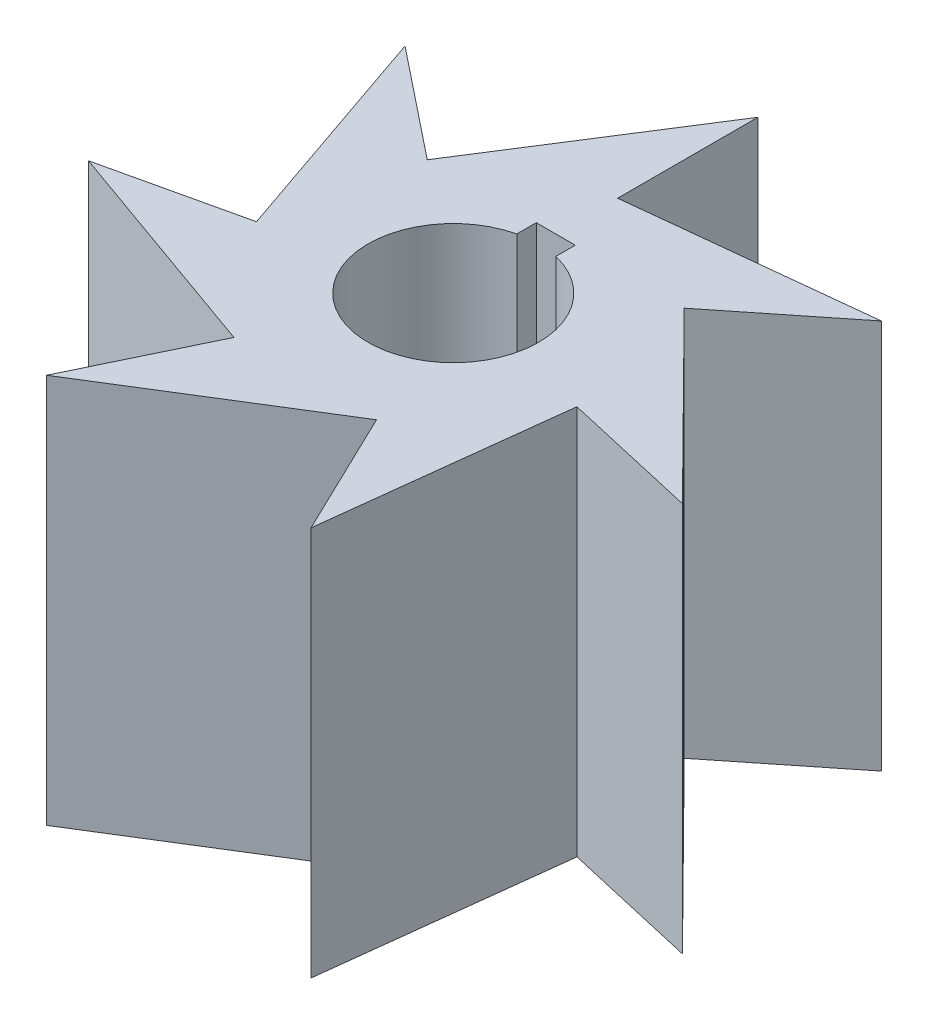
SolidWorks part; units mm, degrees
ref_plane "Front Plane" through (0, 0, 0) normal (0, 0, 1) x (1, 0, 0)
ref_plane "Top Plane" through (0, 0, 0) normal (0, 1, 0) x (1, 0, 0)
ref_plane "Right Plane" through (0, 0, 0) normal (1, 0, 0) x (0, 0, -1)
sketch "Sketch1" plane through (0, 0, 0) normal (0, 1, 0) x (1, 0, 0)
  line L0 (0, 33.7214) -> (0, 62.5)
  line L1 (26.3645, 21.025) -> (48.8645, 38.9681)
  line L2 (32.876, -7.5037) -> (60.933, -13.9076)
  line L3 (14.6312, -30.3819) -> (27.1177, -56.3106)
  line L4 (-14.6312, -30.3819) -> (-27.1177, -56.3106)
  line L5 (-32.876, -7.5037) -> (-60.933, -13.9076)
  line L6 (-26.3645, 21.025) -> (-48.8645, 38.9681)
  line L7 (-26.3645, 21.025) -> (0, 62.5)
  line L8 (0, 33.7214) -> (48.8645, 38.9681)
  line L9 (26.3645, 21.025) -> (60.933, -13.9076)
  line L10 (32.876, -7.5037) -> (27.1177, -56.3106)
  line L11 (14.6312, -30.3819) -> (-27.1177, -56.3106)
  line L12 (-14.6312, -30.3819) -> (-60.933, -13.9076)
  line L13 (-32.876, -7.5037) -> (-48.8645, 38.9681)
  line L14 (-4, 17.0367) -> (-4, 21.0367)
  line L15 (-4, 21.0367) -> (4, 21.0367)
  line L16 (4, 21.0367) -> (4, 17.0367)
  arc A1 (-4, 17.0367) -> (4, 17.0367) centre (0, 0) ccw
  point P7 (0, 21.0367)
  dimension "D1" = 7
  dimension "D6" = 35
  dimension "D2" = 51.429
  dimension "D3" = 22.5
  dimension "D5" = 4
  dimension "D7" = 8
  dimension "D4" = 7
extrude "Boss-Extrude1" add sketch "Sketch1" along normal blind 80
